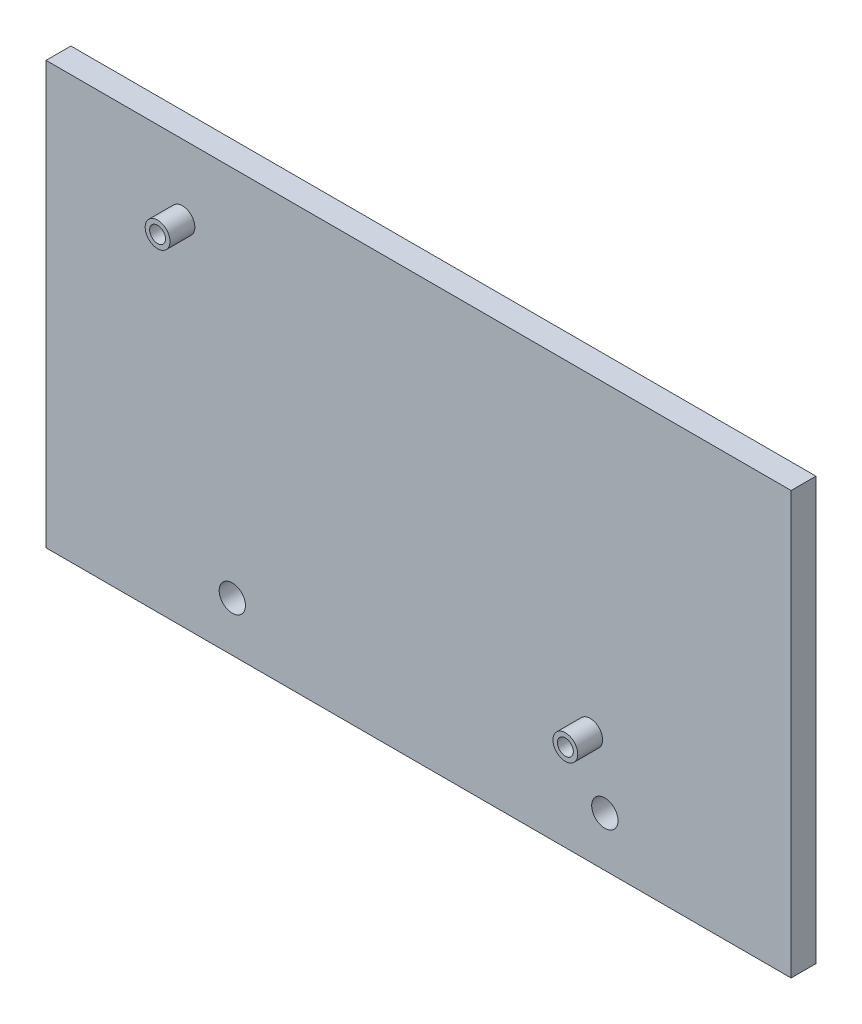
SolidWorks part; units mm, degrees
ref_plane "Front Plane" through (0, 0, 0) normal (0, 0, 1) x (1, 0, 0)
ref_plane "Top Plane" through (0, 0, 0) normal (0, 1, 0) x (1, 0, 0)
ref_plane "Right Plane" through (0, 0, 0) normal (1, 0, 0) x (0, 0, -1)
sketch "Sketch1" plane through (0, 0, 0) normal (0, 0, 1) x (1, 0, 0)
  line L17 (20, 20) -> (130, 20)
  line L18 (20, 20) -> (20, 80)
  line L19 (20, 80) -> (130, 80)
  line L20 (130, 20) -> (130, 80)
  line L21 (0, 0) -> (150, 0)
  line L22 (0, 0) -> (0, 85)
  line L23 (0, 85) -> (150, 85)
  line L24 (150, 0) -> (150, 85)
  circle A0 centre (37.5, 10) radius 2.65
  circle A1 centre (112.5, 10) radius 2.65
  dimension "D5" = 5.3
  dimension "D8" = 5.3
  dimension "D1" = 20
  dimension "D2" = 20
  dimension "D3" = 5
  dimension "D4" = 20
  dimension "D6" = 110
  dimension "D7" = 60
  dimension "D9" = 75
  dimension "D10" = 37.5
  dimension "D11" = 37.5
  dimension "D12" = 10
extrude "Boss-Extrude1" add sketch "Sketch1" along normal blind 5 contours L22 L21 L24 L23 | A0 | A1
sketch "Sketch2" plane through (0, 0, 5) normal (0, 0, 1) x (1, 0, 0)
  line L0 (27.4544, 70.8762) -> (24.25, 70.8762)
  line L1 (24.25, 80.4) -> (125.75, 80.4)
  line L2 (24.25, 80.4) -> (24.25, 20)
  line L3 (24.25, 20) -> (125.75, 20)
  line L4 (125.75, 80.4) -> (125.75, 20)
  line L5 (24.25, 70.8762) -> (27.4544, 70.8762)
  line L6 (27.4544, 70.8762) -> (27.4544, 80.4)
  line L7 (109.5494, 22.54) -> (109.5494, 20)
  line L8 (109.5494, 22.54) -> (125.75, 22.54)
  line L9 (20, 20) -> (130, 20) construction
  line L10 (20, 80) -> (130, 80) construction
  line L11 (150, 0) -> (150, 85) construction
  circle A0 centre (27.4544, 70.8762) radius 1.6
  circle A1 centre (109.5494, 22.54) radius 1.6
  point P18 (75, 80.4)
  dimension "D14" = 3.2
  dimension "D15" = 3.2
  dimension "D1" = 9.5238
  dimension "D2" = 3.2044
  dimension "D3" = 60.4
  dimension "D4" = 101.5
  dimension "D5" = 16.2006
  dimension "D6" = 2.54
  dimension "D7" = 0
  dimension "D8" = 0.4
  dimension "D9" = 75
  dimension "D10" = 9.5238
  dimension "D11" = 3.2044
  dimension "D12" = 16.2006
  dimension "D13" = 2.54
extrude "Cut-Extrude1" cut sketch "Sketch2" against normal blind 5 contours L0 A0 L6 | L6 A0 L0 | L7 A1 L8 | L8 A1 L7
sketch "Sketch3" plane through (0, 0, 5) normal (0, 0, 1) x (1, 0, 0)
  circle A0 centre (27.4544, 70.8762) radius 2.5
  circle A1 centre (27.4544, 70.8762) radius 1.6
  circle A2 centre (109.5494, 22.54) radius 1.6
  circle A3 centre (109.5494, 22.54) radius 2.5
  dimension "D1" = 3.2
  dimension "D2" = 5
  dimension "D3" = 3.2
  dimension "D4" = 5
extrude "Boss-Extrude2" add sketch "Sketch3" along normal blind 5
sketch "Sketch4" plane through (0, 0, 0) normal (0, 0, -1) x (-1, 0, 0)
  circle A0 centre (-27.4544, 70.8762) radius 3
  circle A1 centre (-27.4544, 70.8762) radius 1.6
  circle A2 centre (-109.5494, 22.54) radius 3
  circle A3 centre (-109.5494, 22.54) radius 1.6
  dimension "D1" = 3.2
  dimension "D2" = 3.2
  dimension "D3" = 6
  dimension "D4" = 6
extrude "Cut-Extrude2" cut sketch "Sketch4" against normal blind 3.2
